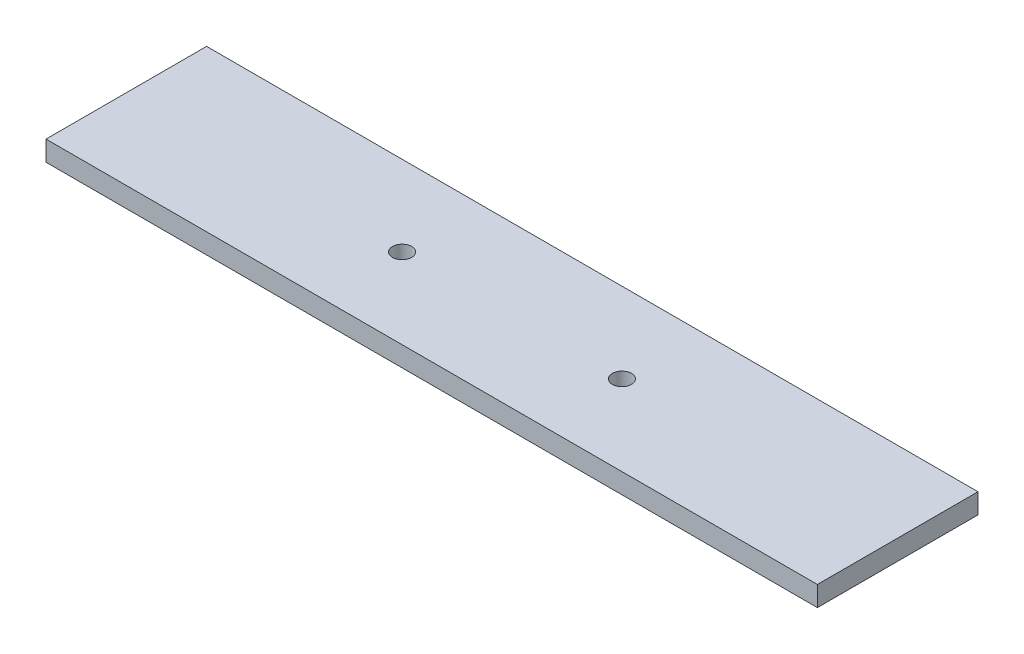
SolidWorks part; units mm, degrees
ref_plane "Front Plane" through (0, 0, 0) normal (0, 0, 1) x (1, 0, 0)
ref_plane "Top Plane" through (0, 0, 0) normal (0, 1, 0) x (1, 0, 0)
ref_plane "Right Plane" through (0, 0, 0) normal (1, 0, 0) x (0, 0, -1)
sketch "Sketch1" plane through (0, 0, 0) normal (0, 1, 0) x (1, 0, 0)
  line L1 (122, 25.4) -> (-122, 25.4)
  line L2 (122, 25.4) -> (122, -25.4)
  line L3 (122, -25.4) -> (-122, -25.4)
  line L4 (-122, 25.4) -> (-122, -25.4)
  line L5 (122, 25.4) -> (-122, -25.4) construction
  line L6 (122, -25.4) -> (-122, 25.4) construction
  point P0 (0, 0)
  dimension "D1" = 50.8
  dimension "D2" = 244
extrude "Boss-Extrude1" add sketch "Sketch1" along normal blind 6.35
sketch "Sketch2" plane through (0, 6.35, 0) normal (0, 1, 0) x (1, 0, 0)
  line L0 (0, -25.4) -> (0, 25.4) construction
  line L1 (-122, -25.4) -> (122, -25.4) construction
  line L2 (122, 25.4) -> (-122, 25.4) construction
  line L3 (-31.75, 0) -> (-31.75, 25.4) construction
  line L4 (31.75, 0) -> (31.75, 25.4) construction
  circle A0 centre (-34.7726, 0) radius 3.0226
  circle A1 centre (34.7726, 0) radius 3.0226
  dimension "D2" = 6.0452
  dimension "D1" = 63.5
extrude "Cut-Extrude1" cut sketch "Sketch2" against normal blind 6.35
equation "\"Rint\"=2.5"
equation "\"D1@Sketch2\"=\"Rint\""
equation "\"DiamTor\"=0.238"
equation "\"D2@Sketch2\"=\"DiamTor\""
